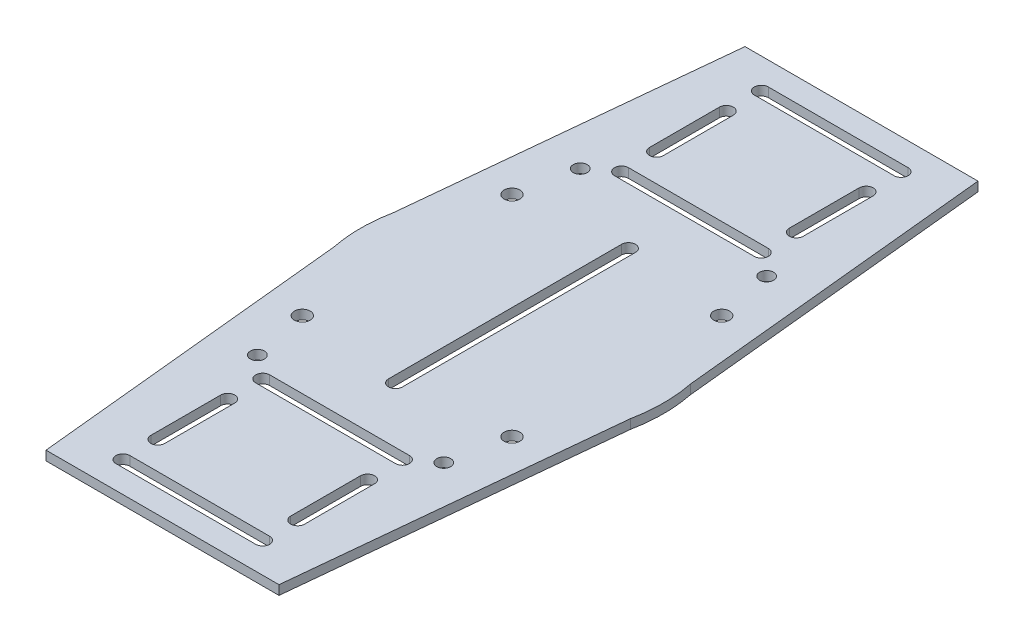
SolidWorks part; units mm, degrees
ref_plane "Front Plane" through (0, 0, 0) normal (0, 0, 1) x (1, 0, 0)
ref_plane "Top Plane" through (0, 0, 0) normal (0, 1, 0) x (1, 0, 0)
ref_plane "Right Plane" through (0, 0, 0) normal (1, 0, 0) x (0, 0, -1)
sketch "Sketch1" plane through (0, 0, 0) normal (0, 1, 0) x (1, 0, 0)
  line L0 (-31.8564, 6.4356) -> (-25, 75)
  line L1 (-25, 75) -> (25, 75)
  line L2 (0, 0) -> (0, 83.1473) construction
  line L3 (-25, -75) -> (25, -75)
  line L4 (0, 0) -> (-46.5144, 0) construction
  line L5 (-25, 75) -> (25, -75) construction
  line L6 (-25, -75) -> (25, 75) construction
  line L7 (-31.8564, -6.4356) -> (-25, -75)
  line L8 (25, 75) -> (31.8564, 6.4356)
  line L9 (31.8564, -6.4356) -> (25, -75)
  line L10 (0, 0) -> (-31.1711, 53.9899) construction
  arc A0 (-31.8564, 6.4356) -> (-31.8564, -6.4356) centre (0, 0) ccw
  arc A1 (31.8564, -6.4356) -> (31.8564, 6.4356) centre (0, 0) ccw
  circle A2 centre (-20, 34.641) radius 1.5
  circle A3 centre (20, 34.641) radius 1.5
  circle A4 centre (20, -34.641) radius 1.5
  circle A5 centre (-20, -34.641) radius 1.5
  point P0 (0, 0)
  dimension "D3" = 60
  dimension "D4" = 40
  dimension "D1" = 50
  dimension "D2" = 150
extrude "Boss-Extrude1" add sketch "Sketch1" along normal blind 2
sketch "Sketch2" plane through (0, 2, 0) normal (0, 1, 0) x (1, 0, 0)
  line L0 (-15, 68.5) -> (15, 68.5) construction
  line L1 (-15, 70) -> (15, 70)
  line L2 (-15, 67) -> (15, 67)
  line L4 (25, 75) -> (-25, 75) construction
  line L5 (0, 0) -> (0, 107) construction
  line L6 (0, 0) -> (-84.2744, 0) construction
  line L7 (-15, -68.5) -> (15, -68.5) construction
  line L8 (-15, -70) -> (15, -70)
  line L9 (-15, -67) -> (15, -67)
  line L10 (0, 53.5) -> (21.3407, 53.5) construction
  line L11 (-15, 38.5) -> (15, 38.5) construction
  line L12 (-15, 37) -> (15, 37)
  line L13 (-15, 40) -> (15, 40)
  line L14 (-15, -38.5) -> (15, -38.5) construction
  line L15 (-15, -37) -> (15, -37)
  line L16 (-15, -40) -> (15, -40)
  line L22 (0, 25) -> (0, -25) construction
  line L23 (1.5, 25) -> (1.5, -25)
  line L24 (-1.5, 25) -> (-1.5, -25)
  arc A0 (-15, 70) -> (-15, 67) centre (-15, 68.5) ccw
  arc A1 (15, 67) -> (15, 70) centre (15, 68.5) ccw
  arc A4 (-15, -70) -> (-15, -67) centre (-15, -68.5) cw
  arc A5 (15, -67) -> (15, -70) centre (15, -68.5) cw
  arc A6 (-15, 37) -> (-15, 40) centre (-15, 38.5) cw
  arc A7 (15, 40) -> (15, 37) centre (15, 38.5) cw
  arc A8 (-15, -37) -> (-15, -40) centre (-15, -38.5) ccw
  arc A9 (15, -40) -> (15, -37) centre (15, -38.5) ccw
  arc A13 (1.5, 25) -> (-1.5, 25) centre (0, 25) ccw
  arc A14 (-1.5, -25) -> (1.5, -25) centre (0, -25) ccw
  point P2 (0, 68.5)
  point P12 (0, -68.5)
  point P13 (0, 75)
  point P26 (0, 38.5)
  point P33 (0, -38.5)
  point P55 (0, 0)
  dimension "D1" = 1.5
  dimension "D3" = 0
  dimension "D10" = 1.5
  dimension "D2" = 30
  dimension "D4" = 5
  dimension "D5" = 30
  dimension "D11" = 50
extrude "Cut-Extrude1" cut sketch "Sketch2" against normal blind 2
sketch "Sketch8" plane through (0, 2, 0) normal (0, 1, 0) x (1, 0, 0)
  line L0 (0, 0) -> (-64.5349, 0) construction
  line L1 (0, 0) -> (0, -59.4258) construction
  line L3 (-22.5, -22.5) -> (22.5, -22.5)
  line L4 (-22.5, -22.5) -> (-22.5, 22.5)
  line L5 (-22.5, 22.5) -> (22.5, 22.5)
  line L6 (22.5, -22.5) -> (22.5, 22.5)
  line L7 (-22.5, -22.5) -> (22.5, 22.5) construction
  line L8 (-22.5, 22.5) -> (22.5, -22.5) construction
  dimension "D1" = 45
  dimension "D2" = 45
hole_wizard "M3 Clearance Hole1" positions "3DSketch1" profile "Sketch9" hole size "M3" standard "ANSI Metric"
sketch3d "3DSketch1"
  point P0 (-22.5, 2, -22.5)
  point P3 (22.5, 2, -22.5)
  point P6 (22.5, 2, 22.5)
  point P9 (-22.5, 2, 22.5)
sketch "Sketch9" plane through (-22.5, 2, -22.5) normal (1, 0, 0) x (0, 0, 1)
  line L0 (0, 0) -> (0, 11.0215)
  line L1 (0, 11.0215) -> (1.7, 10)
  line L2 (1.7, 10) -> (1.7, 0)
  line L5 (1.7, 0) -> (0, 0)
  line L10 (0, 11.0215) -> (-1.7, 10) construction
  line L11 (0, -6.35) -> (0, 107.95) construction
  dimension "Hole Dia." = 3.4
  dimension "Hole Depth" = 10
  dimension "Drill Angle" = 118
sketch "Sketch11" plane through (0, 2, 0) normal (0, 1, 0) x (1, 0, 0)
  line L0 (0, 0) -> (-95.88, 0) construction
  line L1 (0, 0) -> (0, -109.0869) construction
  line L3 (15, -46) -> (15, -61) construction
  line L10 (16.5, -46) -> (16.5, -61)
  line L11 (13.5, -46) -> (13.5, -61)
  line L12 (-15, -46) -> (-15, -61) construction
  line L13 (-16.5, -46) -> (-16.5, -61)
  line L14 (-13.5, -46) -> (-13.5, -61)
  line L15 (-15, 46) -> (-15, 61) construction
  line L16 (-16.5, 46) -> (-16.5, 61)
  line L17 (-13.5, 46) -> (-13.5, 61)
  line L18 (15, 46) -> (15, 61) construction
  line L19 (16.5, 46) -> (16.5, 61)
  line L20 (13.5, 46) -> (13.5, 61)
  arc A0 (16.5, -46) -> (13.5, -46) centre (15, -46) ccw
  arc A1 (13.5, -61) -> (16.5, -61) centre (15, -61) ccw
  arc A2 (-16.5, -46) -> (-13.5, -46) centre (-15, -46) cw
  arc A3 (-13.5, -61) -> (-16.5, -61) centre (-15, -61) cw
  arc A4 (-16.5, 46) -> (-13.5, 46) centre (-15, 46) ccw
  arc A5 (-13.5, 61) -> (-16.5, 61) centre (-15, 61) ccw
  arc A6 (16.5, 46) -> (13.5, 46) centre (15, 46) cw
  arc A7 (13.5, 61) -> (16.5, 61) centre (15, 61) cw
  point P8 (0, -53.5)
  point P13 (15, -53.5)
  point P18 (-15, -53.5)
  point P25 (-15, 53.5)
  point P32 (15, 53.5)
  dimension "D3" = 1.5
  dimension "D1" = 30
  dimension "D2" = 15
extrude "Cut-Extrude4" cut sketch "Sketch11" against normal blind 10
